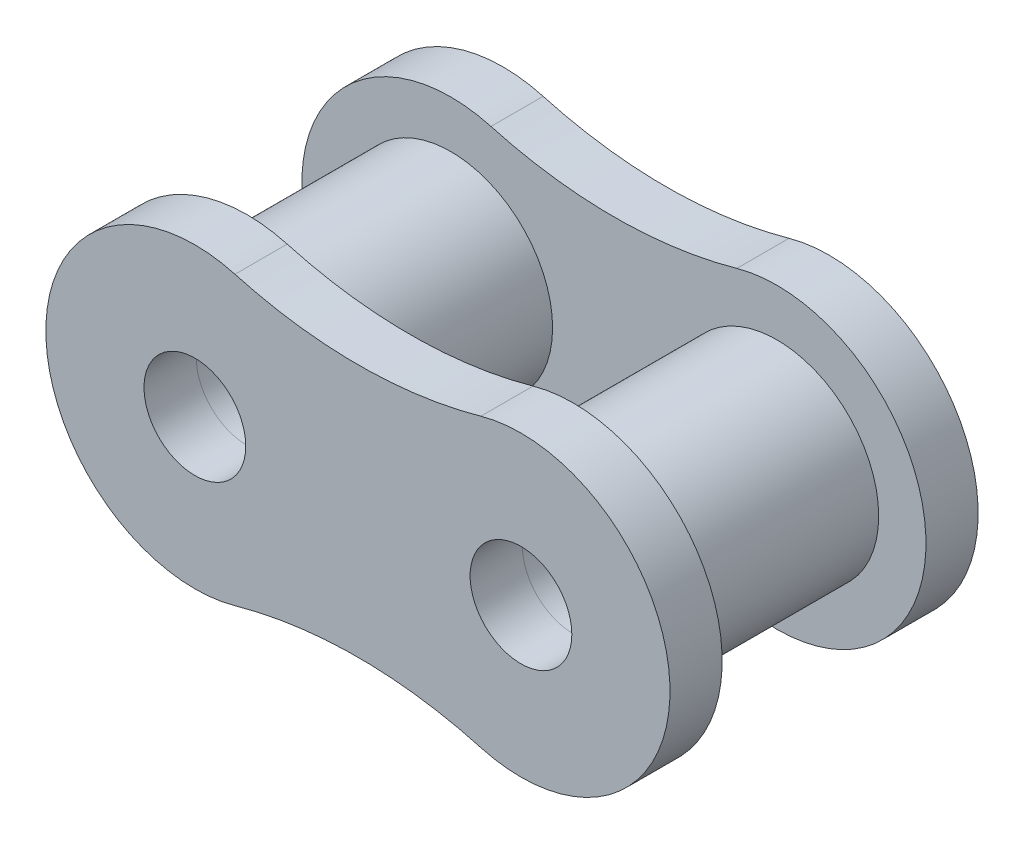
SolidWorks part; units mm, degrees
ref_plane "Front Plane" through (0, 0, 0) normal (0, 0, 1) x (1, 0, 0)
ref_plane "Top Plane" through (0, 0, 0) normal (0, 1, 0) x (1, 0, 0)
ref_plane "Right Plane" through (0, 0, 0) normal (1, 0, 0) x (0, 0, -1)
sketch "Sketch1" plane through (0, 0, 0) normal (0, 0, 1) x (1, 0, 0)
  line L0 (-6.35, 0) -> (6.35, 0) construction
  line L1 (-6.35, 5.8039) -> (-6.35, -5.8039) construction
  line L2 (0, -4.9333) -> (0, 4.9333) construction
  line L3 (6.35, -5.8039) -> (6.35, 5.8039) construction
  circle A0 centre (-6.35, 0) radius 3.9624
  circle A1 centre (6.35, 0) radius 3.9624
  circle A2 centre (-6.35, 0) radius 1.9812
  circle A3 centre (6.35, 0) radius 1.9812
  arc A4 (-4.7879, 5.5897) -> (-4.7879, -5.5897) centre (-6.35, 0) ccw
  arc A5 (4.7879, -5.5897) -> (4.7879, 5.5897) centre (6.35, 0) ccw
  arc A6 (-4.7879, 5.5897) -> (4.7879, 5.5897) centre (0, 22.723) ccw
  arc A7 (-4.7879, -5.5897) -> (4.7879, -5.5897) centre (0, -22.723) cw
  dimension "Roller Dia" = 7.9248
  dimension "Pin Dia" = 3.9624
  dimension "Pitch" = 12.7
  dimension "H" = 11.6078
  dimension "D2" = 9.8666
sketch "Sketch2" plane through (0, 0, 0) normal (0, 1, 0) x (1, 0, 0)
  line L0 (0, 3.9688) -> (0, -3.9688) construction
  point P2 (0, -6.0008)
  point P4 (0, 6.0008)
  point P5 (0, 6.0515)
  point P6 (0, 8.0836)
  dimension "W" = 7.9375
  dimension "T" = 2.032
  dimension "D1" = 2.032
  dimension "D2" = 2.032
  dimension "D3" = 0.0508
ref_plane "Plane1" through (0, 0, 3.9688) normal (0, 0, 1) x (1, 0, 0)
ref_plane "Plane2" through (0, 0, -6.0515) normal (0, 0, 1) x (1, 0, 0)
sketch "Sketch4" plane through (0, 0, 0) normal (0, 0, 1) x (1, 0, 0)
  circle A0 centre (-6.35, 0) radius 3.9624 construction
  circle A1 centre (-6.35, 0) radius 3.9624
  circle A2 centre (6.35, 0) radius 3.9624 construction
  circle A3 centre (6.35, 0) radius 3.9624
  circle A4 centre (-6.35, 0) radius 2.0066
  circle A5 centre (6.35, 0) radius 2.0066
  dimension "D1" = 4.0132
  dimension "D2" = 4.0132
extrude "Boss-Extrude1" add sketch "Sketch4" along normal mid plane 7.9375
sketch "Sketch5" plane through (0, 0, 3.9688) normal (0, 0, 1) x (1, 0, 0)
  arc A0 (-4.7879, 5.5897) -> (-4.7879, -5.5897) centre (-6.35, 0) ccw construction
  arc A1 (-4.7879, 5.5897) -> (4.7879, 5.5897) centre (0, 22.723) ccw construction
  circle A2 centre (-6.35, 0) radius 1.9812 construction
  arc A3 (4.7879, -5.5897) -> (4.7879, 5.5897) centre (6.35, 0) ccw construction
  circle A4 centre (6.35, 0) radius 1.9812 construction
  arc A5 (4.7879, -5.5897) -> (-4.7879, -5.5897) centre (0, -22.723) ccw construction
  arc A6 (-4.7879, 5.5897) -> (-4.7879, -5.5897) centre (-6.35, 0) ccw
  arc A7 (-4.7879, 5.5897) -> (4.7879, 5.5897) centre (0, 22.723) ccw
  circle A8 centre (-6.35, 0) radius 1.9812
  arc A9 (4.7879, -5.5897) -> (4.7879, 5.5897) centre (6.35, 0) ccw
  circle A10 centre (6.35, 0) radius 1.9812
  arc A11 (4.7879, -5.5897) -> (-4.7879, -5.5897) centre (0, -22.723) ccw
extrude "Boss-Extrude2" add sketch "Sketch5" along normal up to vertex (2.032 mm away) separate body up to point (0, 0, 6.0008)
mirror "Mirror3" about plane through (0, 0, 0) normal (0, 0, 1) of bodies 103
combine bodies "Combine2" operation type add bodies to combine 120 103 102 101
ref_plane "Plane3" through (0, 0, 0) normal (0, 0, 1) x (1, 0, 0)
equation "\"D2@Sketch1\" =\"H@Sketch1\"*.85"
equation "\"D1@Sketch2\" = \"T@Sketch2\""
equation "\"D1@Sketch4\" = \"Pin Dia@Sketch1\"+.002"
equation "\"D2@Sketch4\" = \"D1@Sketch4\""
equation "\"D1@Boss-Extrude1\" = \"W@Sketch2\""
equation "\"D2@Sketch2\" = \"T@Sketch2\""
